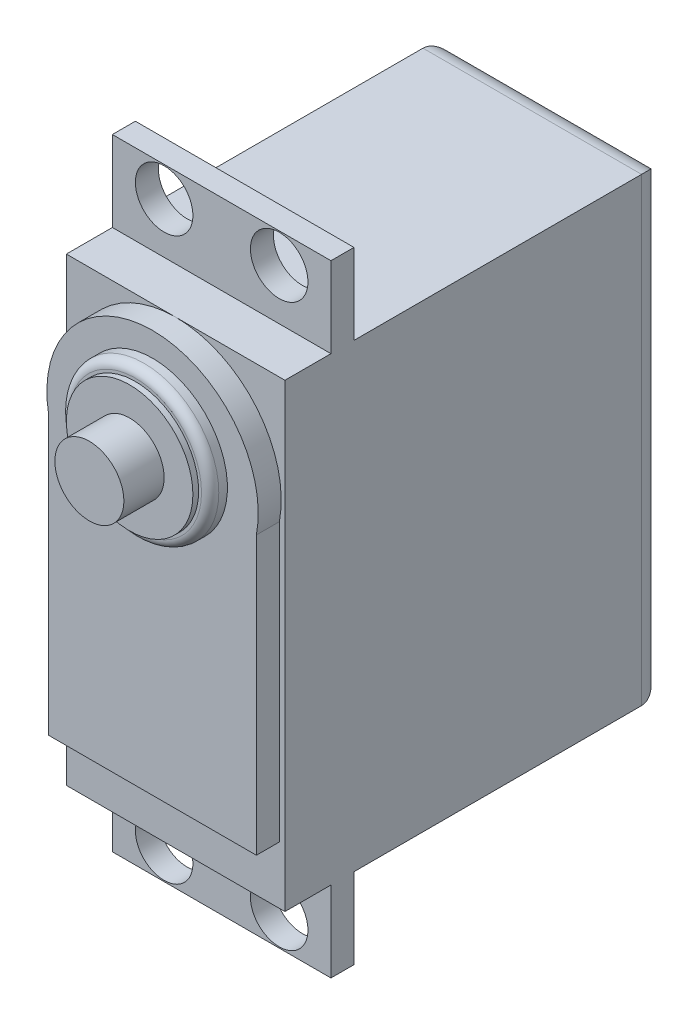
SolidWorks part; units mm, degrees
ref_plane "Plan de face" through (0, 0, 0) normal (0, 0, 1) x (1, 0, 0)
ref_plane "Plan de dessus" through (0, 0, 0) normal (0, 1, 0) x (1, 0, 0)
ref_plane "Plan de droite" through (0, 0, 0) normal (1, 0, 0) x (0, 0, -1)
sketch "Esquisse1" plane through (0, 0, 0) normal (1, 0, 0) x (0, 0, -1)
  line L0 (0, 0) -> (4, 0)
  line L1 (4, 0) -> (4, -7)
  line L2 (4, -7) -> (6, -7)
  line L3 (6, -7) -> (6, 0)
  line L4 (6, 0) -> (33, 0)
  line L5 (33, 0) -> (33, 40)
  line L6 (0, 0) -> (0, 40)
  line L7 (0, 20) -> (33, 20) construction
  line L8 (6, 40) -> (33, 40)
  line L9 (6, 47) -> (6, 40)
  line L10 (4, 47) -> (6, 47)
  line L11 (4, 40) -> (4, 47)
  line L12 (0, 40) -> (4, 40)
  dimension "D1" = 33
  dimension "D2" = 4
  dimension "D3" = 2
  dimension "D4" = 20
  dimension "D5" = 7
extrude "Boss.-Extru.1" add sketch "Esquisse1" along normal mid plane 19
ref_plane "Plan1" through (0, 0, -4) normal (0, 0, 1) x (1, 0, 0)
sketch "Esquisse3" plane through (0, 0, -4) normal (0, 0, 1) x (1, 0, 0)
  line L0 (-9.5, 20) -> (9.5, 20) construction
  line L1 (-9.5, 40) -> (-9.5, 0) construction
  line L2 (9.5, 40) -> (9.5, 0) construction
  line L3 (0, 47) -> (0, 20) construction
  line L4 (9.5, 47) -> (-9.5, 47) construction
  circle A0 centre (5, 44.4) radius 2.5
  circle A1 centre (-5, 44.4) radius 2.5
  circle A2 centre (5, -4.4) radius 2.5
  circle A3 centre (-5, -4.4) radius 2.5
  dimension "D1" = 5
  dimension "D2" = 2.6
  dimension "D3" = 4.5
extrude "Enlèv. mat.-Extru.40" cut sketch "Esquisse3" against normal blind 10
sketch "Esquisse4" plane through (0, 0, 0) normal (0, 0, 1) x (1, 0, 0)
  line L0 (-9.0349, 5) -> (9.0189, 5)
  line L1 (9.0189, 5) -> (9.0189, 29.1109)
  line L2 (-9.0349, 5) -> (-9.0349, 29.1109)
  line L3 (9.5, 0) -> (-9.5, 0) construction
  arc A0 (-9.0349, 29.1109) -> (9.0189, 29.1109) centre (-0.008, 30.8138) cw
  dimension "D1" = 5
extrude "Boss.-Extru.2" add sketch "Esquisse4" along normal blind 2
fillet "Congé1" radius 2 4 edges at (0, 0, -33) (9.5, 20, -33) (0, 40, -33) (-9.5, 20, -33)
sketch "Esquisse5" plane through (0, 0, 2) normal (0, 0, 1) x (1, 0, 0)
  circle A0 centre (0, 31.4091) radius 6.5
  dimension "D1" = 13
extrude "Boss.-Extru.3" add sketch "Esquisse5" along normal blind 1.5
fillet "Congé2" radius 0.75 1 edges at (6.5, 31.4091, 3.5)
sketch "Esquisse6" plane through (0, 0, 3.5) normal (0, 0, 1) x (1, 0, 0)
  circle A0 centre (0, 31.4091) radius 5.5
  dimension "D1" = 11
extrude "Boss.-Extru.4" add sketch "Esquisse6" along normal blind 0.5
sketch "Esquisse7" plane through (0, 0, 4) normal (0, 0, 1) x (1, 0, 0)
  circle A0 centre (0, 31.4091) radius 3
  dimension "D1" = 6
extrude "Boss.-Extru.5" add sketch "Esquisse7" along normal blind 3.5
